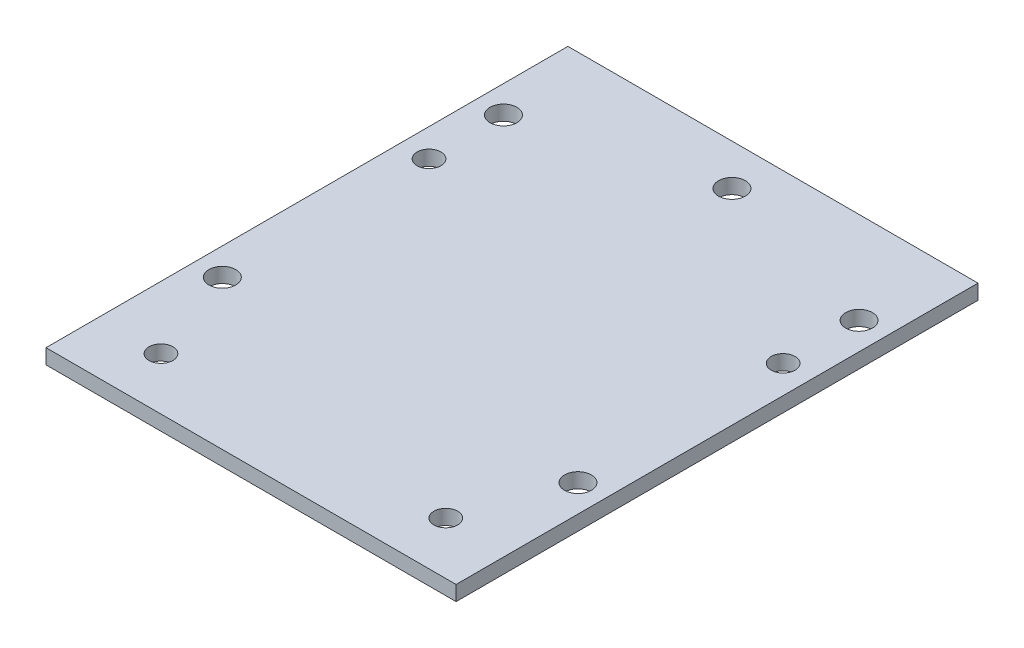
SolidWorks part; units mm, degrees
ref_plane "Front Plane" through (0, 0, 0) normal (0, 0, 1) x (1, 0, 0)
ref_plane "Top Plane" through (0, 0, 0) normal (0, 1, 0) x (1, 0, 0)
ref_plane "Right Plane" through (0, 0, 0) normal (1, 0, 0) x (0, 0, -1)
sketch "Sketch1" plane through (0, 0, 0) normal (0, 1, 0) x (1, 0, 0)
  line L0 (0.4946, 28.5881) -> (0.4946, -41.4119) construction
  line L1 (-27.0054, 28.5881) -> (27.9946, 28.5881)
  line L2 (-27.0054, 28.5881) -> (-27.0054, -41.4119)
  line L3 (-27.0054, -41.4119) -> (27.9946, -41.4119)
  line L4 (27.9946, 28.5881) -> (27.9946, -41.4119)
  line L5 (-18.6054, -34.3949) -> (19.5946, -34.3949) construction
  line L6 (-23.2554, 6.2051) -> (24.2446, 6.2051) construction
  circle A0 centre (19.5946, -34.3949) radius 1.6
  circle A1 centre (-18.6054, -34.3949) radius 1.6
  circle A2 centre (24.2446, 6.2051) radius 1.6
  circle A4 centre (-23.2554, 6.2051) radius 1.6
  circle A5 centre (24.3446, -21.4119) radius 1.8
  circle A6 centre (-23.3554, -21.4119) radius 1.8
  circle A7 centre (24.3446, 16.2881) radius 1.8
  circle A8 centre (-23.3554, 16.2881) radius 1.8
  circle A9 centre (0.4946, 23.0865) radius 1.8
  point P24 (0, 0)
  point P25 (0, 0)
  dimension "D3" = 3.2
  dimension "D5" = 3.2
  dimension "D8" = 23.75
  dimension "D7" = 23.75
  dimension "D10" = 3.6
  dimension "D13" = 23.85
  dimension "D15" = 37.7
  dimension "D17" = 23.85
  dimension "D19" = 3.6
  dimension "D1" = 55
  dimension "D2" = 70
  dimension "D4" = 19.1
  dimension "D6" = 19.1
  dimension "D9" = 40.6
  dimension "D11" = 23.85
  dimension "D12" = 50
  dimension "D14" = 50
  dimension "D16" = 23.85
  dimension "D18" = 37.7
  dimension "D20" = 24.8
extrude "Boss-Extrude1" add sketch "Sketch1" along normal blind 2
